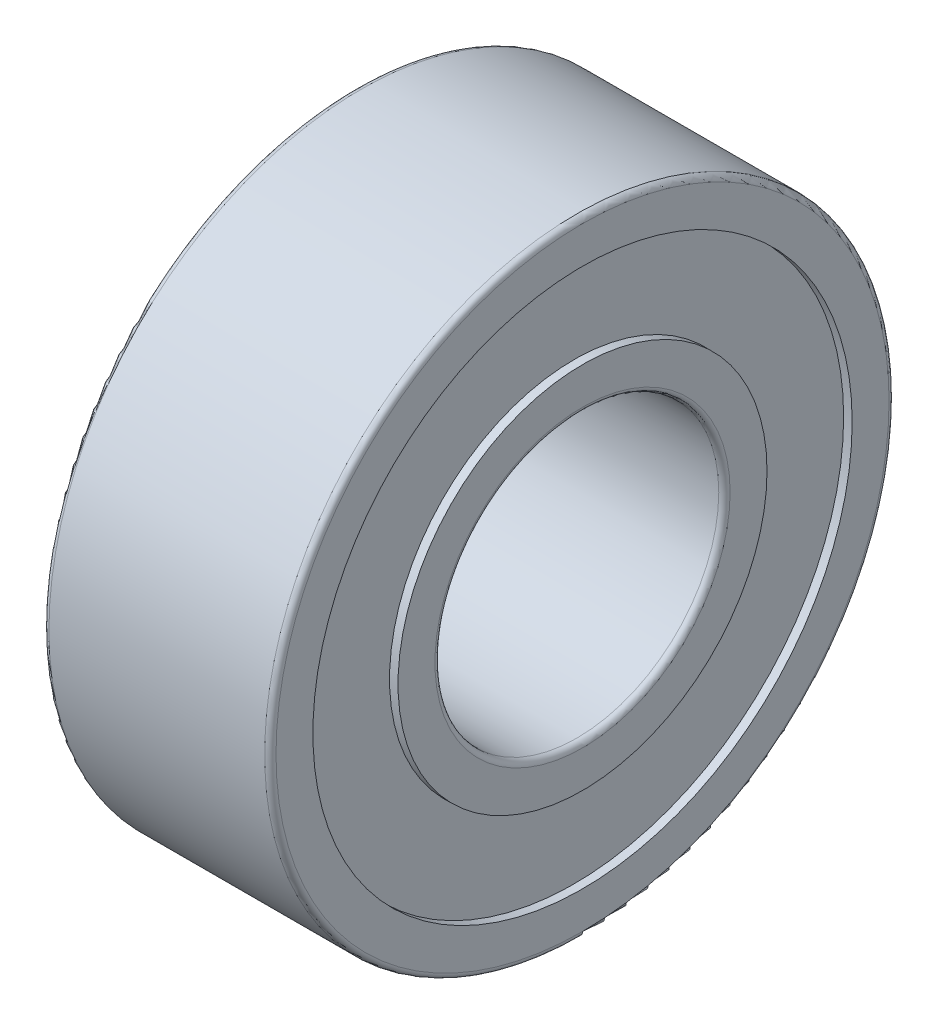
SolidWorks part; units mm, degrees
material "Plain Carbon Steel"
ref_plane "Front Plane" through (0, 0, 0) normal (0, 0, 1) x (1, 0, 0)
ref_plane "Top Plane" through (0, 0, 0) normal (0, 1, 0) x (1, 0, 0)
ref_plane "Right Plane" through (0, 0, 0) normal (1, 0, 0) x (0, 0, -1)
sketch "Sketch1" plane through (0, 0, 0) normal (0, 0, 1) x (1, 0, 0)
  line L0 (4, 5) -> (-4, 5)
  line L1 (-4, 5) -> (-4, 6.5)
  line L2 (-4, 6.5) -> (-3.7, 6.5)
  line L3 (-3.7, 6.5) -> (-3.7, 9.5)
  line L4 (-3.7, 9.5) -> (-4, 9.5)
  line L5 (-4, 9.5) -> (-4, 11)
  line L6 (-4, 11) -> (4, 11)
  line L7 (0, 11) -> (0, 5) construction
  line L8 (4, 9.5) -> (4, 11)
  line L9 (3.7, 9.5) -> (4, 9.5)
  line L10 (3.7, 6.5) -> (3.7, 9.5)
  line L11 (4, 6.5) -> (3.7, 6.5)
  line L12 (4, 5) -> (4, 6.5)
  line L13 (0, 0) -> (-4.3663, 0) construction
  dimension "D1" = 10
  dimension "D2" = 22
  dimension "D3" = 8
  dimension "D4" = 1.5
  dimension "D5" = 1.5
  dimension "D6" = 0.3
revolve "Revolve1" add sketch "Sketch1" angle 360 about L13
fillet "Fillet1" radius 0.2 4 edges at (-4, 0, -11) (4, 0, -11) (-4, 0, -5) (4, 0, -5)
